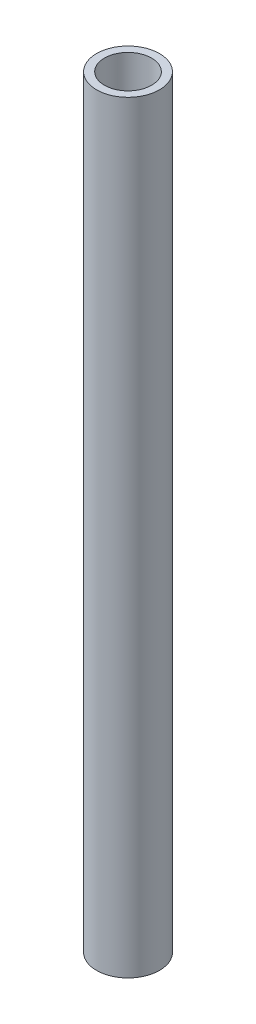
SolidWorks part; units mm, degrees
material "Сталь 08Х21Н5Т ГОСТ 5632-72"
ref_plane "Спереди" through (0, 0, 0) normal (0, 0, 1) x (1, 0, 0)
ref_plane "Сверху" through (0, 0, 0) normal (0, 1, 0) x (1, 0, 0)
ref_plane "Справа" through (0, 0, 0) normal (1, 0, 0) x (0, 0, -1)
other "Configuration Table"
sketch "Эскиз1" plane through (0, 0, 0) normal (0, 1, 0) x (1, 0, 0)
  circle A0 centre (0, 0) radius 4
  circle A1 centre (0, 0) radius 3
  dimension "D1" = 6
  dimension "D2" = 8
extrude "Бобышка-Вытянуть1" add sketch "Эскиз1" along normal blind 97
